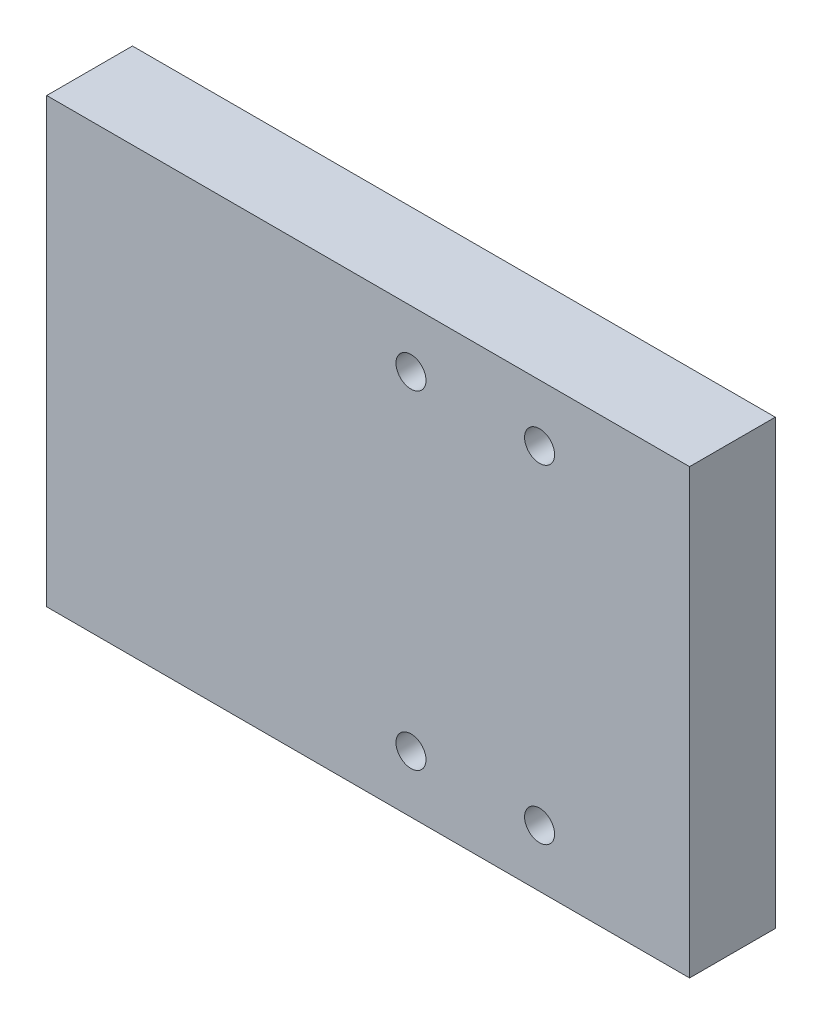
SolidWorks part; units mm, degrees
material "1.0037 (S235JR)"
ref_plane "Płaszczyzna przednia" through (0, 0, 0) normal (0, 0, 1) x (1, 0, 0)
ref_plane "Płaszczyzna górna" through (0, 0, 0) normal (0, 1, 0) x (1, 0, 0)
ref_plane "Płaszczyzna prawa" through (0, 0, 0) normal (1, 0, 0) x (0, 0, -1)
sketch "Szkic1" plane through (0, 0, 0) normal (0, 0, 1) x (1, 0, 0)
  line L0 (8, 300) -> (28, 300) construction
  line L1 (28, 331) -> (118, 331)
  line L2 (28, 331) -> (28, 269)
  line L3 (28, 269) -> (118, 269)
  line L4 (118, 331) -> (118, 269)
  line L5 (8, 592) -> (8, 8) construction
  dimension "D1" = 62
  dimension "D2" = 90
  dimension "D3" = 20
extrude "Dodanie-wyciągnięcie1" add sketch "Szkic1" along normal blind 12
hole_wizard "Otwór gwintowany M5x0.81" positions "Szkic3" profile "Szkic2" tap size "M5x0.8" standard "Ansi Metric"
sketch "Szkic3" plane through (0, 0, 12) normal (0, 0, 1) x (1, 0, 0)
  circle A0 centre (97, 277) radius 2.75 construction
  point P0 (97, 323)
  point P3 (79, 323)
  point P6 (79, 277)
  point P9 (97, 277)
sketch "Szkic2" plane through (97, 323, 12) normal (1, 0, 0) x (0, -1, 0)
  line L0 (0, 0) -> (0, 15.2618)
  line L1 (0, 15.2618) -> (2.1, 14)
  line L2 (2.1, 14) -> (2.1, 0)
  line L5 (2.1, 0) -> (0, 0)
  line L10 (0, 15.2618) -> (-2.1, 14) construction
  line L11 (0, -6.35) -> (0, 107.95) construction
  dimension "Średnica wiertła gwintu" = 4.2
  dimension "Głębokość otworu gwintowanego" = 14
  dimension "Kąt wiertła" = 118
hole_wizard "Otwór gwintowany M5x0.82" positions "Szkic5" profile "Szkic4" tap size "M5x0.8" standard "Ansi Metric"
sketch "Szkic5" plane through (28, 0, 0) normal (-1, 0, 0) x (0, 0, 1)
  point P0 (6, 286)
  point P3 (6, 314)
sketch "Szkic4" plane through (28, 286, 6) normal (0, 1, 0) x (0, 0, 1)
  line L0 (0, 0) -> (0, 21.2618)
  line L1 (0, 21.2618) -> (2.1, 20)
  line L2 (2.1, 20) -> (2.1, 0)
  line L5 (2.1, 0) -> (0, 0)
  line L10 (0, 21.2618) -> (-2.1, 20) construction
  line L11 (0, -6.35) -> (0, 107.95) construction
  dimension "Średnica wiertła gwintu" = 4.2
  dimension "Głębokość otworu gwintowanego" = 20
  dimension "Kąt wiertła" = 118
